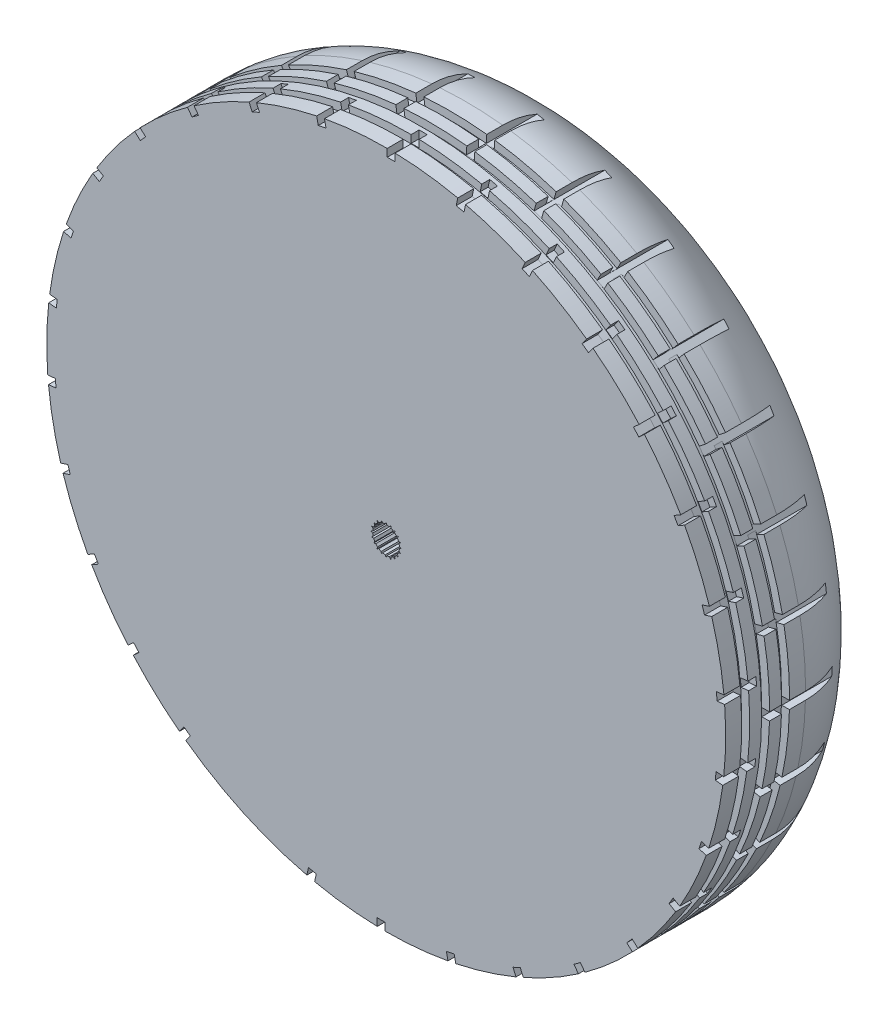
SolidWorks part; units mm, degrees
material "BUTYL"
ref_plane "Front Plane" through (0, 0, 0) normal (0, 0, 1) x (1, 0, 0)
ref_plane "Top Plane" through (0, 0, 0) normal (0, 1, 0) x (1, 0, 0)
ref_plane "Right Plane" through (0, 0, 0) normal (1, 0, 0) x (0, 0, -1)
sketch "Sketch1" plane through (0, 0, 0) normal (0, 0, 1) x (1, 0, 0)
  circle A0 centre (0, 0) radius 107.95
  dimension "D1" = 215.9
extrude "Boss-Extrude1" add sketch "Sketch1" along normal blind 25.4
sketch "Sketch3" plane through (0, 0, 0) normal (0, 1, 0) x (1, 0, 0)
  line L0 (107.95, 0) -> (-107.95, 0) construction
  line L1 (-107.95, 0) -> (107.95, 0)
  line L2 (0, 50.8) -> (0, 0) construction
  ellipse E0 centre (0, 0) end of major axis (107.95, 0) minor radius 50.8 (107.95, 0) -> (-107.95, 0) ccw
revolve "Revolve1" add sketch "Sketch3" angle 360 about L2
sketch "Sketch5" plane through (0, 0, 25.4) normal (0, 0, 1) x (1, 0, 0)
  line L2 (0, 0) -> (0, 5.5832) construction
  line L3 (0, 0) -> (0, -5.1917) construction
  line L4 (-0.049, 4.8251) -> (0.2017, 4.2077)
  line L5 (-0.049, 4.8251) -> (-0.2998, 4.2077)
  line L6 (1.4528, 4.5872) -> (1.5005, 3.9225)
  line L7 (1.4528, 4.5872) -> (1.0235, 4.0775)
  line L8 (2.8076, 3.8969) -> (2.6476, 3.25)
  line L9 (2.8076, 3.8969) -> (2.2418, 3.5448)
  line L10 (3.8828, 2.8217) -> (3.5307, 2.2559)
  line L11 (3.8828, 2.8217) -> (3.2359, 2.6617)
  line L12 (4.5731, 1.4669) -> (4.0634, 1.0376)
  line L13 (4.5731, 1.4669) -> (3.9084, 1.5146)
  line L14 (4.811, -0.0349) -> (4.1936, -0.2857)
  line L15 (4.811, -0.0349) -> (4.1936, 0.2158)
  line L16 (4.5731, -1.5367) -> (3.9084, -1.5844)
  line L17 (4.5731, -1.5367) -> (4.0634, -1.1075)
  line L18 (3.8828, -2.8916) -> (3.2359, -2.7315)
  line L19 (3.8828, -2.8916) -> (3.5307, -2.3258)
  line L20 (2.8076, -3.9667) -> (2.2418, -3.6146)
  line L21 (2.8076, -3.9667) -> (2.6476, -3.3199)
  line L22 (1.4528, -4.6571) -> (1.0235, -4.1474)
  line L23 (1.4528, -4.6571) -> (1.5005, -3.9924)
  line L24 (-0.049, -4.8949) -> (-0.2998, -4.2775)
  line L25 (-0.049, -4.8949) -> (0.2017, -4.2775)
  line L26 (-1.5508, -4.6571) -> (-1.5985, -3.9924)
  line L27 (-1.5508, -4.6571) -> (-1.1216, -4.1474)
  line L28 (-2.9057, -3.9667) -> (-2.7456, -3.3199)
  line L29 (-2.9057, -3.9667) -> (-2.3399, -3.6146)
  line L30 (-3.9808, -2.8916) -> (-3.6287, -2.3258)
  line L31 (-3.9808, -2.8916) -> (-3.334, -2.7315)
  line L32 (-4.6712, -1.5367) -> (-4.1615, -1.1075)
  line L33 (-4.6712, -1.5367) -> (-4.0065, -1.5844)
  line L34 (-4.909, -0.0349) -> (-4.2916, 0.2158)
  line L35 (-4.909, -0.0349) -> (-4.2916, -0.2857)
  line L36 (-4.6712, 1.4669) -> (-4.0065, 1.5146)
  line L37 (-4.6712, 1.4669) -> (-4.1615, 1.0376)
  line L38 (-3.9808, 2.8217) -> (-3.334, 2.6617)
  line L39 (-3.9808, 2.8217) -> (-3.6287, 2.2559)
  line L40 (-2.9057, 3.8969) -> (-2.3399, 3.5448)
  line L41 (-2.9057, 3.8969) -> (-2.7456, 3.25)
  line L42 (-1.5508, 4.5872) -> (-1.1216, 4.0775)
  line L43 (-1.5508, 4.5872) -> (-1.5985, 3.9225)
  arc A3 (-1.5985, 3.9225) -> (-2.3399, 3.5448) centre (-0.049, -0.0349) ccw
  arc A4 (-0.2998, 4.2077) -> (-1.1216, 4.0775) centre (-0.049, -0.0349) ccw
  arc A5 (1.0235, 4.0775) -> (0.2017, 4.2077) centre (-0.049, -0.0349) ccw
  arc A6 (2.2418, 3.5448) -> (1.5005, 3.9225) centre (-0.049, -0.0349) ccw
  arc A7 (3.2359, 2.6617) -> (2.6476, 3.25) centre (-0.049, -0.0349) ccw
  arc A8 (3.9084, 1.5146) -> (3.5307, 2.2559) centre (-0.049, -0.0349) ccw
  arc A9 (4.1936, 0.2158) -> (4.0634, 1.0376) centre (-0.049, -0.0349) ccw
  arc A10 (4.0634, -1.1075) -> (4.1936, -0.2857) centre (-0.049, -0.0349) ccw
  arc A11 (3.5307, -2.3258) -> (3.9084, -1.5844) centre (-0.049, -0.0349) ccw
  arc A12 (2.6476, -3.3199) -> (3.2359, -2.7315) centre (-0.049, -0.0349) ccw
  arc A13 (1.5005, -3.9924) -> (2.2418, -3.6146) centre (-0.049, -0.0349) ccw
  arc A14 (0.2017, -4.2775) -> (1.0235, -4.1474) centre (-0.049, -0.0349) ccw
  arc A15 (-1.1216, -4.1474) -> (-0.2998, -4.2775) centre (-0.049, -0.0349) ccw
  arc A16 (-2.3399, -3.6146) -> (-1.5985, -3.9924) centre (-0.049, -0.0349) ccw
  arc A17 (-3.334, -2.7315) -> (-2.7456, -3.3199) centre (-0.049, -0.0349) ccw
  arc A18 (-4.0065, -1.5844) -> (-3.6287, -2.3258) centre (-0.049, -0.0349) ccw
  arc A19 (-4.2916, -0.2857) -> (-4.1615, -1.1075) centre (-0.049, -0.0349) ccw
  arc A20 (-4.1615, 1.0376) -> (-4.2916, 0.2158) centre (-0.049, -0.0349) ccw
  arc A21 (-3.6287, 2.2559) -> (-4.0065, 1.5146) centre (-0.049, -0.0349) ccw
  arc A22 (-2.7456, 3.25) -> (-3.334, 2.6617) centre (-0.049, -0.0349) ccw
  point P1 (0, 0)
  point P66 (-0.049, -0.0349)
  point P67 (0, 0)
  dimension "D1" = 8.5
extrude "Cut-Extrude1" cut sketch "Sketch5" against normal blind 6
ref_plane "Plane1" through (0, 0, 12.7) normal (0, 0, 1) x (1, 0, 0)
sketch "Sketch6" plane through (0, 0, 12.7) normal (0, 0, 1) x (1, 0, 0)
  circle A0 centre (0, 0) radius 107.95
  circle A1 centre (0, 0) radius 105.41
  dimension "D1" = 210.82
extrude "Cut-Extrude2" cut sketch "Sketch6" against normal mid plane 2.54
pattern_linear "LPattern1" count 2 spacing 6.35 along (0, 0, 1) count 2 spacing 6.35 along (0, 0, -1) of "Cut-Extrude2"
sketch "Sketch9" plane through (0, 0, 12.7) normal (0, 0, 1) x (1, 0, 0)
  line L0 (25.2624, 105.0942) -> (24.7344, 102.6097)
  line L1 (0, 105.51) -> (0.3201, 105.51) construction
  line L2 (0.3201, 105.51) -> (2.8601, 105.51)
  line L3 (0.3201, 105.51) -> (0.3201, 108.05)
  line L4 (0.3201, 108.05) -> (2.8601, 108.05)
  line L5 (2.8601, 108.05) -> (2.8601, 105.51)
  line L6 (22.2499, 103.1378) -> (24.7344, 102.6097)
  line L7 (22.2499, 103.1378) -> (22.778, 105.6223)
  line L8 (22.778, 105.6223) -> (25.2624, 105.0942)
  line L9 (46.5607, 97.5453) -> (45.5276, 95.2249)
  line L10 (43.2072, 96.258) -> (45.5276, 95.2249)
  line L11 (43.2072, 96.258) -> (44.2403, 98.5784)
  line L12 (44.2403, 98.5784) -> (46.5607, 97.5453)
  line L13 (65.8241, 85.7332) -> (64.3311, 83.6783)
  line L14 (62.2762, 85.1712) -> (64.3311, 83.6783)
  line L15 (62.2762, 85.1712) -> (63.7692, 87.2261)
  line L16 (63.7692, 87.2261) -> (65.8241, 85.7332)
  line L17 (82.2106, 70.1741) -> (80.323, 68.4745)
  line L18 (78.6234, 70.3621) -> (80.323, 68.4745)
  line L19 (78.6234, 70.3621) -> (80.511, 72.0617)
  line L20 (80.511, 72.0617) -> (82.2106, 70.1741)
  line L21 (95.0041, 51.5481) -> (92.8044, 50.2781)
  line L22 (91.5344, 52.4778) -> (92.8044, 50.2781)
  line L23 (91.5344, 52.4778) -> (93.7341, 53.7478)
  line L24 (93.7341, 53.7478) -> (95.0041, 51.5481)
  line L25 (103.6455, 30.6692) -> (101.2298, 29.8843)
  line L26 (100.4449, 32.3) -> (101.2298, 29.8843)
  line L27 (100.4449, 32.3) -> (102.8606, 33.0849)
  line L28 (102.8606, 33.0849) -> (103.6455, 30.6692)
  line L29 (107.7571, 8.4499) -> (105.231, 8.1844)
  line L30 (104.9655, 10.7105) -> (105.231, 8.1844)
  line L31 (104.9655, 10.7105) -> (107.4916, 10.976)
  line L32 (107.4916, 10.976) -> (107.7571, 8.4499)
  line L33 (107.1591, -14.1387) -> (104.6331, -13.8732)
  line L34 (104.8986, -11.3471) -> (104.6331, -13.8732)
  line L35 (104.8986, -11.3471) -> (107.4246, -11.6126)
  line L36 (107.4246, -11.6126) -> (107.1591, -14.1387)
  line L37 (101.8778, -36.1094) -> (99.4622, -35.3245)
  line L38 (100.2471, -32.9088) -> (99.4622, -35.3245)
  line L39 (100.2471, -32.9088) -> (102.6628, -33.6937)
  line L40 (102.6628, -33.6937) -> (101.8778, -36.1094)
  line L41 (92.144, -56.5019) -> (89.9443, -55.2319)
  line L42 (91.2143, -53.0322) -> (89.9443, -55.2319)
  line L43 (91.2143, -53.0322) -> (93.414, -54.3022)
  line L44 (93.414, -54.3022) -> (92.144, -56.5019)
  line L45 (78.383, -74.425) -> (76.4954, -72.7254)
  line L46 (78.195, -70.8378) -> (76.4954, -72.7254)
  line L47 (78.195, -70.8378) -> (80.0826, -72.5374)
  line L48 (80.0826, -72.5374) -> (78.383, -74.425)
  line L49 (61.1963, -89.0954) -> (59.7034, -87.0405)
  line L50 (61.7583, -85.5475) -> (59.7034, -87.0405)
  line L51 (61.7583, -85.5475) -> (63.2512, -87.6024)
  line L52 (63.2512, -87.6024) -> (61.1963, -89.0954)
  line L53 (41.3351, -99.8719) -> (40.302, -97.5515)
  line L54 (42.6224, -96.5184) -> (40.302, -97.5515)
  line L55 (42.6224, -96.5184) -> (43.6555, -98.8388)
  line L56 (43.6555, -98.8388) -> (41.3351, -99.8719)
  line L57 (19.6673, -106.2835) -> (19.1392, -103.799)
  line L58 (21.6237, -103.2709) -> (19.1392, -103.799)
  line L59 (21.6237, -103.2709) -> (22.1518, -105.7554)
  line L60 (22.1518, -105.7554) -> (19.6673, -106.2835)
  line L61 (-2.8601, -108.05) -> (-2.8601, -105.51)
  line L62 (-0.3201, -105.51) -> (-2.8601, -105.51)
  line L63 (-0.3201, -105.51) -> (-0.3201, -108.05)
  line L64 (-0.3201, -108.05) -> (-2.8601, -108.05)
  line L65 (-25.2624, -105.0942) -> (-24.7344, -102.6097)
  line L66 (-22.2499, -103.1378) -> (-24.7344, -102.6097)
  line L67 (-22.2499, -103.1378) -> (-22.778, -105.6223)
  line L68 (-22.778, -105.6223) -> (-25.2624, -105.0942)
  line L69 (-46.5607, -97.5453) -> (-45.5276, -95.2249)
  line L70 (-43.2072, -96.258) -> (-45.5276, -95.2249)
  line L71 (-43.2072, -96.258) -> (-44.2403, -98.5784)
  line L72 (-44.2403, -98.5784) -> (-46.5607, -97.5453)
  line L73 (-65.8241, -85.7332) -> (-64.3311, -83.6783)
  line L74 (-62.2762, -85.1712) -> (-64.3311, -83.6783)
  line L75 (-62.2762, -85.1712) -> (-63.7692, -87.2261)
  line L76 (-63.7692, -87.2261) -> (-65.8241, -85.7332)
  line L77 (-82.2106, -70.1741) -> (-80.323, -68.4745)
  line L78 (-78.6234, -70.3621) -> (-80.323, -68.4745)
  line L79 (-78.6234, -70.3621) -> (-80.511, -72.0617)
  line L80 (-80.511, -72.0617) -> (-82.2106, -70.1741)
  line L81 (-95.0041, -51.5481) -> (-92.8044, -50.2781)
  line L82 (-91.5344, -52.4778) -> (-92.8044, -50.2781)
  line L83 (-91.5344, -52.4778) -> (-93.7341, -53.7478)
  line L84 (-93.7341, -53.7478) -> (-95.0041, -51.5481)
  line L85 (-103.6455, -30.6692) -> (-101.2298, -29.8843)
  line L86 (-100.4449, -32.3) -> (-101.2298, -29.8843)
  line L87 (-100.4449, -32.3) -> (-102.8606, -33.0849)
  line L88 (-102.8606, -33.0849) -> (-103.6455, -30.6692)
  line L89 (-107.7571, -8.4499) -> (-105.231, -8.1844)
  line L90 (-104.9655, -10.7105) -> (-105.231, -8.1844)
  line L91 (-104.9655, -10.7105) -> (-107.4916, -10.976)
  line L92 (-107.4916, -10.976) -> (-107.7571, -8.4499)
  line L93 (-107.1591, 14.1387) -> (-104.6331, 13.8732)
  line L94 (-104.8986, 11.3471) -> (-104.6331, 13.8732)
  line L95 (-104.8986, 11.3471) -> (-107.4246, 11.6126)
  line L96 (-107.4246, 11.6126) -> (-107.1591, 14.1387)
  line L97 (-101.8778, 36.1094) -> (-99.4622, 35.3245)
  line L98 (-100.2471, 32.9088) -> (-99.4622, 35.3245)
  line L99 (-100.2471, 32.9088) -> (-102.6628, 33.6937)
  line L100 (-102.6628, 33.6937) -> (-101.8778, 36.1094)
  line L101 (-92.144, 56.5019) -> (-89.9443, 55.2319)
  line L102 (-91.2143, 53.0322) -> (-89.9443, 55.2319)
  line L103 (-91.2143, 53.0322) -> (-93.414, 54.3022)
  line L104 (-93.414, 54.3022) -> (-92.144, 56.5019)
  line L105 (-78.383, 74.425) -> (-76.4954, 72.7254)
  line L106 (-78.195, 70.8378) -> (-76.4954, 72.7254)
  line L107 (-78.195, 70.8378) -> (-80.0826, 72.5374)
  line L108 (-80.0826, 72.5374) -> (-78.383, 74.425)
  line L109 (-61.1963, 89.0954) -> (-59.7034, 87.0405)
  line L110 (-61.7583, 85.5475) -> (-59.7034, 87.0405)
  line L111 (-61.7583, 85.5475) -> (-63.2512, 87.6024)
  line L112 (-63.2512, 87.6024) -> (-61.1963, 89.0954)
  line L113 (-41.3351, 99.8719) -> (-40.302, 97.5515)
  line L114 (-42.6224, 96.5184) -> (-40.302, 97.5515)
  line L115 (-42.6224, 96.5184) -> (-43.6555, 98.8388)
  line L116 (-43.6555, 98.8388) -> (-41.3351, 99.8719)
  line L117 (-19.6673, 106.2835) -> (-19.1392, 103.799)
  line L118 (-21.6237, 103.2709) -> (-19.1392, 103.799)
  line L119 (-21.6237, 103.2709) -> (-22.1518, 105.7554)
  line L120 (-22.1518, 105.7554) -> (-19.6673, 106.2835)
  circle A0 centre (0, 0) radius 107.95 construction
  point P125 (0, 0)
  dimension "D1" = 30
  dimension "D3" = 2.54
  dimension "D4" = 2.54
extrude "Cut-Extrude4" cut sketch "Sketch9" against normal blind 10.16 from surface at 12.7 contours L5 L2 L3 L4 | L117 L118 L119 L120 | L113 L114 L115 L116 | L109 L110 L111 L112 | L105 L106 L107 L108 | L101 L102 L103 L104 | L97 L98 L99 L100 | L93 L94 L95 L96 | L89 L90 L91 L92 | L85 L86 L87 L88 | L81 L82 L83 L84 | L77 L78 L79 L80 | L73 L74 L75 L76 | L65 L66 L67 L68 | L61 L62 L63 L64 | L57 L58 L59 L60 | L53 L54 L55 L56 | L49 L50 L51 L52 | L45 L46 L47 L48 | L41 L42 L43 L44 | L37 L38 L39 L40 | L33 L34 L35 L36 | L29 L30 L31 L32 | L21 L22 L23 L24 | L25 L26 L27 L28 | L17 L18 L19 L20 | L13 L14 L15 L16 | L9 L10 L11 L12 | L0 L6 L7 L8 starting at face at (-0.049, -0.0349, 25.4)
sketch "Sketch11" plane through (0, 0, 11.43) normal (0, 0, 1) x (1, 0, 0)
  line L0 (7.3106, 104.996) -> (11.4837, 104.7054) construction
  line L1 (34.0539, 103.7014) -> (33.0023, 100.0298)
  line L2 (7.3106, 104.996) -> (14.0314, 104.5281) construction
  line L3 (11.4837, 104.7054) -> (14.0314, 104.5281)
  line L4 (14.0314, 104.5281) -> (14.2966, 108.3381)
  line L5 (14.2966, 108.3381) -> (11.749, 108.5154)
  line L6 (11.749, 108.5154) -> (11.4837, 104.7054)
  line L7 (33.0023, 100.0298) -> (35.4574, 99.3266)
  line L8 (35.4574, 99.3266) -> (36.509, 102.9982)
  line L9 (36.509, 102.9982) -> (34.0539, 103.7014)
  line L10 (54.8705, 94.355) -> (53.0784, 90.9823)
  line L11 (53.0784, 90.9823) -> (55.3337, 89.7841)
  line L12 (55.3337, 89.7841) -> (57.1257, 93.1568)
  line L13 (57.1257, 93.1568) -> (54.8705, 94.355)
  line L14 (73.2889, 80.885) -> (70.8348, 77.9585)
  line L15 (70.8348, 77.9585) -> (72.7917, 76.3175)
  line L16 (72.7917, 76.3175) -> (75.2457, 79.244)
  line L17 (75.2457, 79.244) -> (73.2889, 80.885)
  line L18 (88.5043, 63.8798) -> (85.4954, 61.5276)
  line L19 (85.4954, 61.5276) -> (87.0683, 59.5156)
  line L20 (87.0683, 59.5156) -> (90.0772, 61.8678)
  line L21 (90.0772, 61.8678) -> (88.5043, 63.8798)
  line L22 (99.8516, 44.0828) -> (96.4194, 42.4075)
  line L23 (96.4194, 42.4075) -> (97.5396, 40.1125)
  line L24 (97.5396, 40.1125) -> (100.9718, 41.7878)
  line L25 (100.9718, 41.7878) -> (99.8516, 44.0828)
  line L26 (106.835, 22.3592) -> (103.1295, 21.4341)
  line L27 (103.1295, 21.4341) -> (103.748, 18.9563)
  line L28 (103.748, 18.9563) -> (107.4535, 19.8814)
  line L29 (107.4535, 19.8814) -> (106.835, 22.3592)
  line L30 (109.1491, -0.3417) -> (105.3322, -0.4761)
  line L31 (105.3322, -0.4761) -> (105.4221, -3.0283)
  line L32 (105.4221, -3.0283) -> (109.239, -2.8939)
  line L33 (109.239, -2.8939) -> (109.1491, -0.3417)
  line L34 (106.6929, -23.0276) -> (102.9315, -22.3655)
  line L35 (102.9315, -22.3655) -> (102.4888, -24.8807)
  line L36 (102.4888, -24.8807) -> (106.2502, -25.5427)
  line L37 (106.2502, -25.5427) -> (106.6929, -23.0276)
  line L38 (99.5737, -44.7071) -> (96.0321, -43.2774)
  line L39 (96.0321, -43.2774) -> (95.0762, -45.6456)
  line L40 (95.0762, -45.6456) -> (98.6177, -47.0752)
  line L41 (98.6177, -47.0752) -> (99.5737, -44.7071)
  line L42 (88.1026, -64.4327) -> (84.9357, -62.2979)
  line L43 (84.9357, -62.2979) -> (83.5083, -64.4155)
  line L44 (83.5083, -64.4155) -> (86.6752, -66.5503)
  line L45 (86.6752, -66.5503) -> (88.1026, -64.4327)
  line L46 (72.7811, -81.3422) -> (70.1272, -78.5957)
  line L47 (70.1272, -78.5957) -> (68.2907, -80.3703)
  line L48 (68.2907, -80.3703) -> (70.9445, -83.1168)
  line L49 (70.9445, -83.1168) -> (72.7811, -81.3422)
  line L50 (54.2786, -94.6967) -> (52.2538, -91.4584)
  line L51 (52.2538, -91.4584) -> (50.0884, -92.8124)
  line L52 (50.0884, -92.8124) -> (52.1133, -96.0507)
  line L53 (52.1133, -96.0507) -> (54.2786, -94.6967)
  line L54 (33.404, -103.9125) -> (32.0966, -100.324)
  line L55 (32.0966, -100.324) -> (29.6971, -101.1982)
  line L56 (29.6971, -101.1982) -> (31.0044, -104.7867)
  line L57 (31.0044, -104.7867) -> (33.404, -103.9125)
  line L58 (11.0694, -108.5869) -> (10.5367, -104.805)
  line L59 (10.5367, -104.805) -> (8.0079, -105.1612)
  line L60 (8.0079, -105.1612) -> (8.5405, -108.9431)
  line L61 (8.5405, -108.9431) -> (11.0694, -108.5869)
  line L62 (-11.749, -108.5154) -> (-11.4837, -104.7054)
  line L63 (-11.4837, -104.7054) -> (-14.0314, -104.5281)
  line L64 (-14.0314, -104.5281) -> (-14.2966, -108.3381)
  line L65 (-14.2966, -108.3381) -> (-11.749, -108.5154)
  line L66 (-34.0539, -103.7014) -> (-33.0023, -100.0298)
  line L67 (-33.0023, -100.0298) -> (-35.4574, -99.3266)
  line L68 (-35.4574, -99.3266) -> (-36.509, -102.9982)
  line L69 (-36.509, -102.9982) -> (-34.0539, -103.7014)
  line L70 (-54.8705, -94.355) -> (-53.0784, -90.9823)
  line L71 (-53.0784, -90.9823) -> (-55.3337, -89.7841)
  line L72 (-55.3337, -89.7841) -> (-57.1257, -93.1568)
  line L73 (-57.1257, -93.1568) -> (-54.8705, -94.355)
  line L74 (-73.2889, -80.885) -> (-70.8348, -77.9585)
  line L75 (-70.8348, -77.9585) -> (-72.7917, -76.3175)
  line L76 (-72.7917, -76.3175) -> (-75.2457, -79.244)
  line L77 (-75.2457, -79.244) -> (-73.2889, -80.885)
  line L78 (-88.5043, -63.8798) -> (-85.4954, -61.5276)
  line L79 (-85.4954, -61.5276) -> (-87.0683, -59.5156)
  line L80 (-87.0683, -59.5156) -> (-90.0772, -61.8678)
  line L81 (-90.0772, -61.8678) -> (-88.5043, -63.8798)
  line L82 (-99.8516, -44.0828) -> (-96.4194, -42.4075)
  line L83 (-96.4194, -42.4075) -> (-97.5396, -40.1125)
  line L84 (-97.5396, -40.1125) -> (-100.9718, -41.7878)
  line L85 (-100.9718, -41.7878) -> (-99.8516, -44.0828)
  line L86 (-106.835, -22.3592) -> (-103.1295, -21.4341)
  line L87 (-103.1295, -21.4341) -> (-103.748, -18.9563)
  line L88 (-103.748, -18.9563) -> (-107.4535, -19.8814)
  line L89 (-107.4535, -19.8814) -> (-106.835, -22.3592)
  line L90 (-109.1491, 0.3417) -> (-105.3322, 0.4761)
  line L91 (-105.3322, 0.4761) -> (-105.4221, 3.0283)
  line L92 (-105.4221, 3.0283) -> (-109.239, 2.8939)
  line L93 (-109.239, 2.8939) -> (-109.1491, 0.3417)
  line L94 (-106.6929, 23.0276) -> (-102.9315, 22.3655)
  line L95 (-102.9315, 22.3655) -> (-102.4888, 24.8807)
  line L96 (-102.4888, 24.8807) -> (-106.2502, 25.5427)
  line L97 (-106.2502, 25.5427) -> (-106.6929, 23.0276)
  line L98 (-99.5737, 44.7071) -> (-96.0321, 43.2774)
  line L99 (-96.0321, 43.2774) -> (-95.0762, 45.6456)
  line L100 (-95.0762, 45.6456) -> (-98.6177, 47.0752)
  line L101 (-98.6177, 47.0752) -> (-99.5737, 44.7071)
  line L102 (-88.1026, 64.4327) -> (-84.9357, 62.2979)
  line L103 (-84.9357, 62.2979) -> (-83.5083, 64.4155)
  line L104 (-83.5083, 64.4155) -> (-86.6752, 66.5503)
  line L105 (-86.6752, 66.5503) -> (-88.1026, 64.4327)
  line L106 (-72.7811, 81.3422) -> (-70.1272, 78.5957)
  line L107 (-70.1272, 78.5957) -> (-68.2907, 80.3703)
  line L108 (-68.2907, 80.3703) -> (-70.9445, 83.1168)
  line L109 (-70.9445, 83.1168) -> (-72.7811, 81.3422)
  line L110 (-54.2786, 94.6967) -> (-52.2538, 91.4584)
  line L111 (-52.2538, 91.4584) -> (-50.0884, 92.8124)
  line L112 (-50.0884, 92.8124) -> (-52.1133, 96.0507)
  line L113 (-52.1133, 96.0507) -> (-54.2786, 94.6967)
  line L114 (-33.404, 103.9125) -> (-32.0966, 100.324)
  line L115 (-32.0966, 100.324) -> (-29.6971, 101.1982)
  line L116 (-29.6971, 101.1982) -> (-31.0044, 104.7867)
  line L117 (-31.0044, 104.7867) -> (-33.404, 103.9125)
  line L118 (-11.0694, 108.5869) -> (-10.5367, 104.805)
  line L119 (-10.5367, 104.805) -> (-8.0079, 105.1612)
  line L120 (-8.0079, 105.1612) -> (-8.5405, 108.9431)
  line L121 (-8.5405, 108.9431) -> (-11.0694, 108.5869)
  circle A1 centre (0, 0) radius 107.95 construction
  point P125 (0, 0)
  dimension "D1" = 30
  dimension "D4" = 3.81
extrude "Cut-Extrude5" cut sketch "Sketch11" against normal blind 58.42
